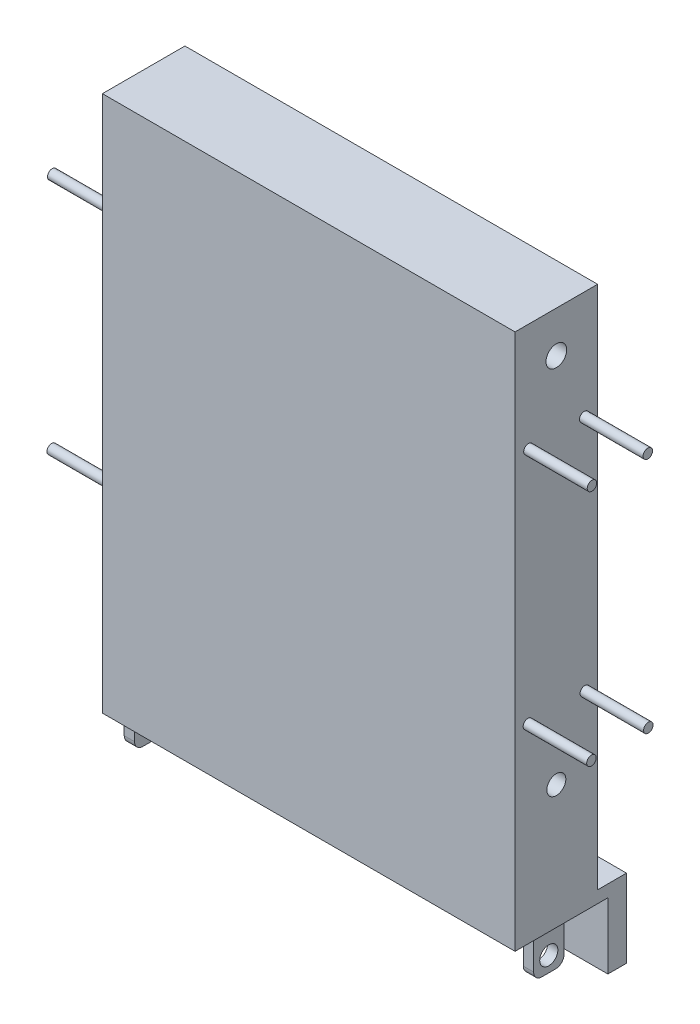
SolidWorks part; units mm, degrees
ref_plane "Front Plane" through (0, 0, 0) normal (0, 0, 1) x (1, 0, 0)
ref_plane "Top Plane" through (0, 0, 0) normal (0, 1, 0) x (1, 0, 0)
ref_plane "Right Plane" through (0, 0, 0) normal (1, 0, 0) x (0, 0, -1)
sketch "Sketch1" plane through (0, 0, 0) normal (0, 0, 1) x (1, 0, 0)
  line L1 (-63.5, 82.55) -> (63.5, 82.55)
  line L2 (-63.5, 82.55) -> (-63.5, -82.55)
  line L3 (-63.5, -82.55) -> (63.5, -82.55)
  line L4 (63.5, 82.55) -> (63.5, -82.55)
  line L5 (-63.5, 82.55) -> (63.5, -82.55) construction
  line L6 (-63.5, -82.55) -> (63.5, 82.55) construction
  point P0 (0, 0)
  dimension "D1" = 165.1
  dimension "D2" = 127
extrude "Boss-Extrude1" add sketch "Sketch1" along normal blind 25.4
sketch "Sketch3" plane through (-63.5, 0, 0) normal (-1, 0, 0) x (0, 0, 1)
  line L0 (25.4, -82.55) -> (0, -82.55) construction
  line L1 (0, 82.55) -> (0, -82.55) construction
  circle A0 centre (12.7, -44.45) radius 2.921
  dimension "D2" = 5.842
  dimension "D3" = 12.7
  dimension "D1" = 38.1
extrude "Cut-Extrude1" cut sketch "Sketch3" against normal blind 10.16
mirror "Mirror1" about plane through (0, 0, 0) normal (1, 0, 0) of "Cut-Extrude1"
sketch "Sketch4" plane through (-63.5, 0, 0) normal (-1, 0, 0) x (0, 0, 1)
  line L0 (12.7, -44.45) -> (12.7, 16.9575) construction
  line L1 (5.885, -25.5499) -> (21.164, -25.5499) construction
  line L2 (0, 82.55) -> (0, -82.55) construction
  circle A0 centre (3.9497, -23.876) radius 1.4605
  circle A1 centre (12.7, -44.45) radius 2.921 construction
  dimension "D2" = 8.7503
  dimension "D3" = 2.921
  dimension "D4" = 3.9497
  dimension "D5" = 20.574
  dimension "D1" = 18.9001
extrude "Boss-Extrude2" add sketch "Sketch4" along normal blind 19.558
sketch "Sketch5" plane through (-63.5, 0, 0) normal (-1, 0, 0) x (0, 0, 1)
  line L0 (3.9497, -23.876) -> (29.4852, -23.876) construction
  circle A0 centre (21.4503, -23.876) radius 1.4605
  circle A2 centre (3.9497, -23.876) radius 1.4605 construction
  dimension "D1" = 2.921
  dimension "D2" = 17.5006
extrude "Boss-Extrude3" add sketch "Sketch5" along normal blind 19.558
mirror "Mirror2" about plane through (0, 0, 0) normal (1, 0, 0) of "Boss-Extrude3", "Boss-Extrude2"
sketch "Sketch6" plane through (0, -82.55, 0) normal (0, -1, 0) x (1, 0, 0)
  line L0 (-63.5, 25.4) -> (-63.5, 0) construction
  line L1 (-62.992, 19.184) -> (-59.818, 19.184)
  line L2 (-62.992, 19.184) -> (-62.992, 9.8434)
  line L3 (-62.992, 9.8434) -> (-59.818, 9.8434)
  line L4 (-59.818, 19.184) -> (-59.818, 9.8434)
  dimension "D1" = 0.508
extrude "Boss-Extrude4" add sketch "Sketch6" along normal blind 11.43
mirror "Mirror3" about plane through (0, 0, 0) normal (1, 0, 0) of "Boss-Extrude4"
sketch "Sketch7" plane through (-62.992, 0, 0) normal (-1, 0, 0) x (0, 0, 1)
  line L0 (19.184, -82.55) -> (9.8434, -82.55) construction
  circle A0 centre (14.5137, -89.281) radius 2.794
  dimension "D1" = 6.731
  dimension "D2" = 5.588
extrude "Cut-Extrude2" cut sketch "Sketch7" against normal through all
sketch "Sketch8" plane through (63.5, 0, 0) normal (1, 0, 0) x (0, 0, -1)
  line L0 (-12.7, -44.45) -> (-12.7, 78.3784) construction
  line L1 (-25.4, 82.55) -> (0, 82.55) construction
  line L2 (-30.1547, 49.276) -> (9.363, 49.276) construction
  circle A0 centre (-12.7, 69.85) radius 3.1875
  dimension "D1" = 12.7
  dimension "D2" = 20.574
extrude "Cut-Extrude4" cut sketch "Sketch8" against normal blind 10.16
sketch "Sketch11" plane through (63.5, 0, 0) normal (1, 0, 0) x (0, 0, -1)
  line L0 (-12.7, 69.85) -> (-12.7, 26.6172) construction
  line L1 (-28.2511, 49.276) -> (9.0127, 49.276) construction
  circle A1 centre (-12.7, 69.85) radius 3.1875 construction
  circle A2 centre (-21.2888, 49.276) radius 1.4605
  dimension "D1" = 20.574
  dimension "D2" = 2.921
extrude "Boss-Extrude5" add sketch "Sketch11" along normal blind 19.558
sketch "Sketch12" plane through (63.5, 0, 0) normal (1, 0, 0) x (0, 0, -1)
  line L0 (-21.2478, 40.7687) -> (-3.7472, 40.7687) construction
  circle A1 centre (-3.7472, 42.926) radius 1.4605
  dimension "D2" = 2.921
  dimension "D1" = 17.5006
sketch "Sketch13" plane through (63.5, 0, 0) normal (1, 0, 0) x (0, 0, -1)
  line L0 (-25.4, 82.55) -> (0, 82.55) construction
  line L1 (-12.7, 82.55) -> (-12.7, -82.55) construction
  line L2 (-25.4, -82.55) -> (0, -82.55) construction
sketch "Sketch14" plane through (-63.5, 0, 0) normal (-1, 0, 0) x (0, 0, 1)
  line L0 (12.7, 82.55) -> (12.7, -82.55) construction
  line L1 (25.4, 82.55) -> (0, 82.55) construction
  line L2 (25.4, -82.55) -> (0, -82.55) construction
ref_plane "Plane1" through (0, 0, 12.7) normal (0, 0, 1) x (1, 0, 0)
mirror "Mirror4" about plane through (0, 0, 12.7) normal (0, 0, 1) of "Boss-Extrude5"
mirror "Mirror6" about plane through (0, 0, 0) normal (1, 0, 0) of "Cut-Extrude4", "Boss-Extrude5", "Mirror4"
fillet "Fillet1" radius 2.54 4 edges at (-61.405, -93.98, 19.184) (-61.405, -93.98, 9.8434) (61.405, -93.98, 9.8434) (61.405, -93.98, 19.184)
sketch "Sketch15" plane through (0, 0, 0) normal (0, 0, -1) x (-1, 0, 0)
  line L0 (63.5, 82.55) -> (63.5, -82.55) construction
  line L1 (-63.5, -82.55) -> (63.5, -82.55)
  line L2 (-63.5, -82.55) -> (-63.5, -78.8409)
  line L3 (-63.5, -78.8409) -> (63.5, -78.8409)
  line L4 (63.5, -82.55) -> (63.5, -78.8409)
extrude "Boss-Extrude6" add sketch "Sketch15" along normal blind 8.89
sketch "Sketch16" plane through (0, -82.55, 0) normal (0, -1, 0) x (1, 0, 0)
  line L0 (-63.5, 25.4) -> (-63.5, -8.89) construction
  line L1 (63.5, -8.89) -> (-63.5, -8.89)
  line L2 (63.5, -8.89) -> (63.5, -3.1586)
  line L3 (63.5, -3.1586) -> (-63.5, -3.1586)
  line L4 (-63.5, -8.89) -> (-63.5, -3.1586)
extrude "Boss-Extrude7" add sketch "Sketch16" along normal blind 20.32
sketch "Sketch17" plane through (-63.5, 0, 0) normal (-1, 0, 0) x (0, 0, 1)
  line L0 (-8.89, -78.8409) -> (0, -78.8409) construction
  line L1 (25.4, 82.55) -> (25.4, -82.55) construction
  circle A0 centre (-6.35, -80.6189) radius 1.4605
  dimension "D1" = 1.778
  dimension "D2" = 31.75
  dimension "D3" = 2.921
extrude "Boss-Extrude8" add sketch "Sketch17" along normal blind 19.558
sketch "Sketch18" plane through (-63.5, 0, 0) normal (-1, 0, 0) x (0, 0, 1)
  line L0 (-6.35, -80.6189) -> (-6.35, -106.5986) construction
  line L1 (-6.35, -106.5986) -> (5.6164, -113.6074) construction
  circle A0 centre (-6.35, -98.1449) radius 1.4605
  circle A1 centre (-6.35, -80.6189) radius 1.4605 construction
  dimension "D1" = 17.526
  dimension "D2" = 2.921
extrude "Boss-Extrude9" add sketch "Sketch18" along normal blind 19.558
